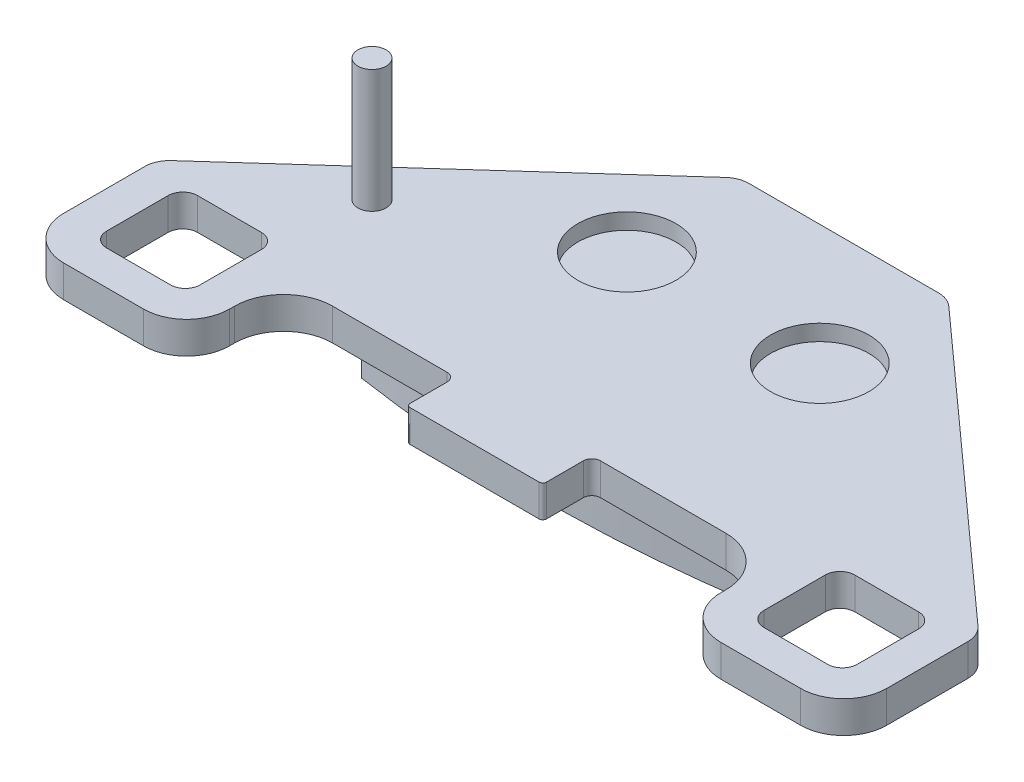
SolidWorks part; units mm, degrees
ref_plane "Front Plane" through (0, 0, 0) normal (0, 0, 1) x (1, 0, 0)
ref_plane "Top Plane" through (0, 0, 0) normal (0, 1, 0) x (1, 0, 0)
ref_plane "Right Plane" through (0, 0, 0) normal (1, 0, 0) x (0, 0, -1)
sketch "Sketch1" plane through (0, 0, 0) normal (0, 1, 0) x (1, 0, 0)
  line L0 (41.7042, -6.5458) -> (11.5195, 20.6205)
  line L1 (-38.1, -21.2725) -> (-29.845, -21.2725)
  line L2 (-42.545, -16.8275) -> (-42.545, -8.4337)
  line L3 (-9.8203, 21.2725) -> (10.795, 21.2725)
  line L4 (42.545, -16.8275) -> (42.545, -8.4337)
  line L7 (37.338, -8.3185) -> (30.734, -8.3185)
  line L8 (38.862, -9.8425) -> (38.862, -16.1925)
  line L9 (37.338, -17.7165) -> (30.734, -17.7165)
  line L10 (29.21, -9.8425) -> (29.21, -16.1925)
  line L11 (-37.211, -8.3185) -> (-30.607, -8.3185)
  line L12 (-38.735, -9.8425) -> (-38.735, -16.1925)
  line L13 (-37.211, -17.7165) -> (-30.607, -17.7165)
  line L14 (-29.083, -9.8425) -> (-29.083, -16.1925)
  line L15 (-9.8203, 21.2725) -> (9.8203, 21.2725)
  line L19 (-42.545, -21.2725) -> (-25.4, -21.2725)
  line L20 (-42.545, -21.2725) -> (-42.545, -7.3025)
  line L22 (-25.4, -16.8275) -> (-25.4, -16.3195)
  line L23 (38.1, -21.2725) -> (29.845, -21.2725)
  line L24 (42.545, -16.8275) -> (42.545, -7.3025)
  line L26 (25.4, -16.8275) -> (25.4, -16.3195)
  line L27 (-41.7042, -6.5458) -> (-11.5195, 20.6205)
  line L28 (7.3692, -11.2395) -> (20.32, -11.2395)
  line L30 (-7.6168, -12.1285) -> (-7.6168, -15.9385)
  line L31 (-7.2358, -16.3195) -> (6.0992, -16.3195)
  line L32 (6.4802, -12.1285) -> (6.4802, -15.9385)
  line L33 (-8.5058, -11.2395) -> (-20.32, -11.2395)
  line L34 (29.845, -21.2725) -> (38.1, -21.2725)
  arc A0 (9.8203, 21.2725) -> (11.5195, 20.6205) centre (9.8203, 18.7325) cw
  arc A1 (-9.8203, 21.2725) -> (-11.5195, 20.6205) centre (-9.8203, 18.7325) ccw
  arc A2 (42.545, -8.4337) -> (41.7042, -6.5458) centre (40.005, -8.4337) ccw
  arc A3 (-42.545, -8.4337) -> (-41.7042, -6.5458) centre (-40.005, -8.4337) cw
  arc A4 (38.1, -21.2725) -> (42.545, -16.8275) centre (38.1, -16.8275) ccw
  arc A5 (29.845, -21.2725) -> (25.4, -16.8275) centre (29.845, -16.8275) cw
  arc A6 (-29.845, -21.2725) -> (-25.4, -16.8275) centre (-29.845, -16.8275) ccw
  arc A7 (-38.1, -21.2725) -> (-42.545, -16.8275) centre (-38.1, -16.8275) cw
  arc A8 (-20.32, -11.2395) -> (-25.4, -16.3195) centre (-20.32, -16.3195) ccw
  arc A9 (20.32, -11.2395) -> (25.4, -16.3195) centre (20.32, -16.3195) cw
  arc A10 (7.3692, -11.2395) -> (6.4802, -12.1285) centre (7.3692, -12.1285) ccw
  arc A11 (-8.5058, -11.2395) -> (-7.6168, -12.1285) centre (-8.5058, -12.1285) cw
  arc A12 (6.0992, -16.3195) -> (6.4802, -15.9385) centre (6.0992, -15.9385) ccw
  arc A13 (-7.6168, -15.9385) -> (-7.2358, -16.3195) centre (-7.2358, -15.9385) ccw
  arc A14 (38.862, -16.1925) -> (37.338, -17.7165) centre (37.338, -16.1925) cw
  arc A15 (37.338, -8.3185) -> (38.862, -9.8425) centre (37.338, -9.8425) cw
  arc A16 (30.734, -8.3185) -> (29.21, -9.8425) centre (30.734, -9.8425) ccw
  arc A17 (30.734, -17.7165) -> (29.21, -16.1925) centre (30.734, -16.1925) cw
  arc A18 (-38.735, -16.1925) -> (-37.211, -17.7165) centre (-37.211, -16.1925) ccw
  arc A19 (-30.607, -17.7165) -> (-29.083, -16.1925) centre (-30.607, -16.1925) ccw
  arc A20 (-30.607, -8.3185) -> (-29.083, -9.8425) centre (-30.607, -9.8425) cw
  arc A21 (-37.211, -8.3185) -> (-38.735, -9.8425) centre (-37.211, -9.8425) ccw
  point P0 (0, 0)
  point P52 (6.4802, -11.2395)
  point P55 (-7.6168, -11.2395)
  point P60 (-7.6168, -16.3195)
  point P63 (38.862, -17.7165)
  point P66 (38.862, -8.3185)
  point P71 (29.21, -17.7165)
  point P74 (-38.735, -17.7165)
  point P77 (-29.083, -17.7165)
  point P82 (-38.735, -8.3185)
  dimension "D7" = 2.54
  dimension "D8" = 2.54
  dimension "D9" = 4.445
  dimension "D10" = 5.08
  dimension "D12" = 0.889
  dimension "D19" = 0.381
  dimension "D20" = 1.524
  dimension "D31" = 23.0332
  dimension "D2" = 14.097
  dimension "D3" = 9.398
  dimension "D4" = 9.652
  dimension "D5" = 9.398
  dimension "D6" = 9.652
  dimension "D11" = 17.145
  dimension "D13" = 3.683
  dimension "D14" = 3.556
  dimension "D15" = 3.556
  dimension "D16" = 3.683
  dimension "D17" = 5.08
  dimension "D18" = 37.592
  dimension "D21" = 29.591
  dimension "D22" = 13.462
  dimension "D23" = 32.512
  dimension "D24" = 40.6093
  dimension "D25" = 41.987
  dimension "D26" = 22.7298
  dimension "D27" = 41.987
  dimension "D28" = 29.21
  dimension "D29" = 8.3185
  dimension "D30" = 29.083
extrude "Boss-Extrude1" add sketch "Sketch1" along normal blind 3.302 contours L30 A13 L31 A12 L32 A10 L28 A9 L26 A5 L23 A4 L4 A2 L0 A0 L3 A1 L27 A3 L2 A7 L1 A6 L22 A8 L33 A11 A21 L11 A20 L14 A19 L13 A18 L12 L9 A17 L10 A16 L7 A15 L8 A14
sketch "Sketch2" plane through (0, 3.302, 0) normal (0, 1, 0) x (1, 0, 0)
sketch "Sketch3" plane through (0, 3.302, 0) normal (0, 1, 0) x (1, 0, 0)
  line L0 (-9.8203, 21.2725) -> (9.8203, 21.2725) construction
  circle A0 centre (-9.9695, 8.8265) radius 5.08
  circle A1 centre (9.9695, 8.8265) radius 5.08
  point P7 (0, 0)
  dimension "D1" = 10.16
  dimension "D2" = 10.16
  dimension "D3" = 19.939
  dimension "D4" = 12.446
  dimension "D5" = 9.9695
extrude "Cut-Extrude1" cut sketch "Sketch3" against normal blind 1.651
sketch "Sketch4" plane through (0, 0, 0) normal (0, -1, 0) x (1, 0, 0)
  line L1 (10.795, -20.1295) -> (-10.795, -20.1295)
  line L2 (20.1295, -11.7284) -> (20.1295, 8.4455)
  line L4 (-20.1295, -11.7284) -> (-20.1295, 8.4455)
  line L5 (-8.5058, 11.2395) -> (-20.32, 11.2395) construction
  line L6 (10.795, -20.1295) -> (-10.795, -20.1295)
  line L10 (10.795, -20.1295) -> (20.1295, -11.7284)
  line L12 (-10.795, -20.1295) -> (-20.1295, -11.7284)
  arc A0 (-20.1295, 8.4455) -> (20.1295, 8.4455) centre (0, -123.7311) cw
  dimension "D1" = 133.7006
  dimension "D9" = 123.7311
  dimension "D10" = 134.9706
  dimension "D2" = 20.1295
  dimension "D3" = 20.1295
  dimension "D4" = 20.1295
  dimension "D5" = 21.59
  dimension "D6" = 22.1836
  dimension "D7" = 22.1836
  dimension "D8" = 131.987
extrude "Boss-Extrude2" add sketch "Sketch4" along normal blind 4.445 contours A0 L4 L12 L1 L10 L2
sketch "Sketch5" plane through (0, 3.302, 0) normal (0, 1, 0) x (1, 0, 0)
  line L0 (-38.1, -21.2725) -> (-29.845, -21.2725) construction
  line L2 (-42.545, -16.8275) -> (-42.545, -8.4337) construction
  circle A0 centre (-27.813, 0.3175) radius 1.4605
  dimension "D1" = 2.921
  dimension "D2" = 21.59
  dimension "D3" = 14.732
extrude "Boss-Extrude3" add sketch "Sketch5" along normal blind 12.7
